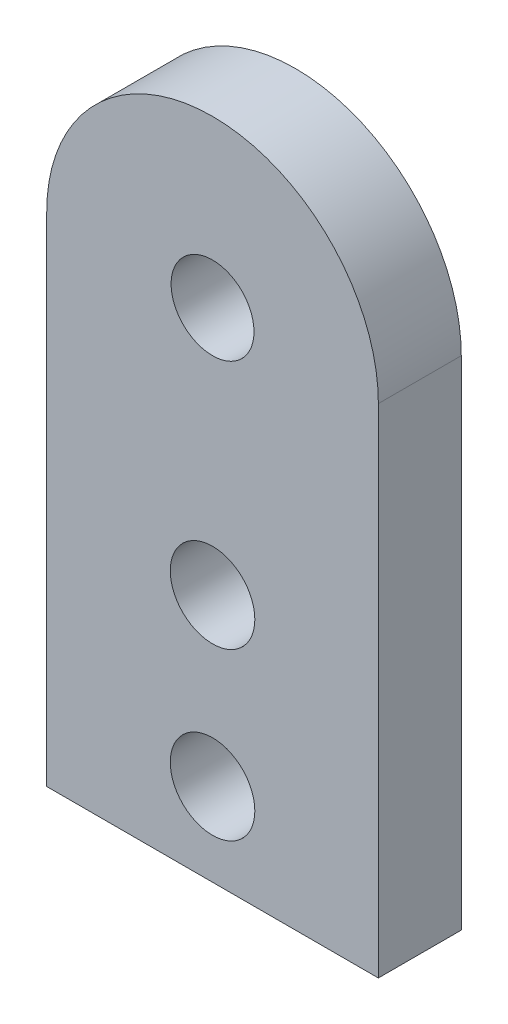
SolidWorks part; units mm, degrees
ref_plane "Front Plane" through (0, 0, 0) normal (0, 0, 1) x (1, 0, 0)
ref_plane "Top Plane" through (0, 0, 0) normal (0, 1, 0) x (1, 0, 0)
ref_plane "Right Plane" through (0, 0, 0) normal (1, 0, 0) x (0, 0, -1)
sketch "Sketch1" plane through (0, 0, 0) normal (0, 0, 1) x (1, 0, 0)
  line L0 (-10, 0) -> (-10, -30)
  line L1 (10, 0) -> (10, -30)
  line L2 (10, -30) -> (-10, -30)
  line L3 (0, -1000) -> (0, 49000) construction
  line L4 (-1002.2178, -10) -> (48997.7822, -10) construction
  arc A0 (10, 0) -> (-10, 0) centre (0, 0) ccw
  circle A1 centre (0, -25) radius 2.55
  circle A2 centre (0, -15) radius 2.55
  dimension "D1" = 20
  dimension "D3" = 5.1
  dimension "D4" = 5.1
  dimension "D5" = 10
  dimension "D6" = 5
  dimension "D2" = 20
  dimension "D7" = 10
extrude "Boss-Extrude1" add sketch "Sketch1" along normal blind 5
sketch "Sketch2" plane through (0, 0, 5) normal (0, 0, 1) x (1, 0, 0)
  circle A0 centre (0, 0) radius 2.5
  dimension "D1" = 5
extrude "Cut-Extrude1" cut sketch "Sketch2" against normal blind 5
